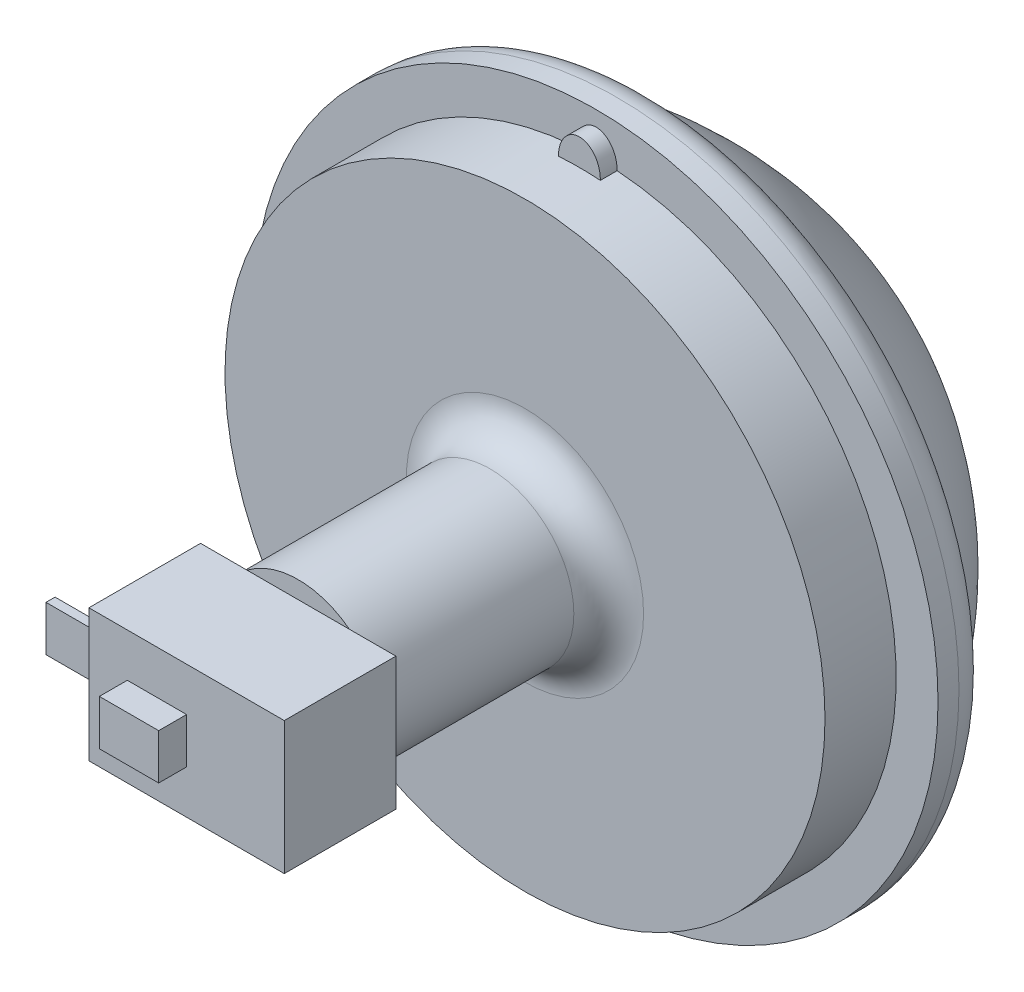
SolidWorks part; units mm, degrees
ref_plane "Front Plane" through (0, 0, 0) normal (0, 0, 1) x (1, 0, 0)
ref_plane "Top Plane" through (0, 0, 0) normal (0, 1, 0) x (1, 0, 0)
ref_plane "Right Plane" through (0, 0, 0) normal (1, 0, 0) x (0, 0, -1)
sketch "Sketch1" plane through (0, 0, 0) normal (0, 0, 1) x (1, 0, 0)
  circle A0 centre (0, 0) radius 49
  dimension "D1" = 98
extrude "Boss-Extrude1" add sketch "Sketch1" against normal blind 8
fillet "Fillet1" radius 5 1 edges at (49, 0, -8)
sketch "Sketch2" plane through (0, 0, 0) normal (0, 0, 1) x (1, 0, 0)
  circle A0 centre (0, 0) radius 43
  dimension "D1" = 86
extrude "Boss-Extrude2" add sketch "Sketch2" along normal blind 10.2
sketch "Sketch3" plane through (0, 0, 10.2) normal (0, 0, 1) x (1, 0, 0)
  circle A0 centre (0, 0) radius 12
  dimension "D1" = 24
extrude "Boss-Extrude3" add sketch "Sketch3" along normal blind 32.5
fillet "Fillet2" radius 5 1 edges at (12, 0, 10.2)
sketch "Sketch4" plane through (0, 0, 42.7) normal (0, 0, 1) x (1, 0, 0)
  line L1 (-14, 9.5) -> (14, 9.5)
  line L2 (-14, 9.5) -> (-14, -9.5)
  line L3 (-14, -9.5) -> (14, -9.5)
  line L4 (14, 9.5) -> (14, -9.5)
  line L5 (-14, 9.5) -> (14, -9.5) construction
  line L6 (-14, -9.5) -> (14, 9.5) construction
  point P0 (0, 0)
  dimension "D1" = 19
  dimension "D2" = 28
extrude "Boss-Extrude4" add sketch "Sketch4" along normal blind 16
sketch "Sketch5" plane through (0, 0, 58.7) normal (0, 0, 1) x (1, 0, 0)
  line L0 (0, 9.5) -> (0, -9.5) construction
  line L1 (14, 9.5) -> (-14, 9.5) construction
  line L2 (-7.3314, -9.5) -> (7.3314, -9.5) construction
  line L3 (-14, -3.25) -> (14, -3.25) construction
  line L4 (-14, 9.5) -> (-14, -9.5) construction
  line L5 (14, -9.5) -> (14, 9.5) construction
  line L6 (-14, 0) -> (14, 0) construction
  line L7 (-14, 3.25) -> (14, 3.25) construction
  line L9 (0, 3.25) -> (-8.5, 3.25)
  line L10 (0, 3.25) -> (0, -3.25)
  line L11 (0, -3.25) -> (-8.5, -3.25)
  line L12 (-8.5, 3.25) -> (-8.5, -3.25)
  point P12 (0, 0)
  dimension "D1" = 3.25
  dimension "D2" = 8.5
extrude "Boss-Extrude5" add sketch "Sketch5" along normal blind 4
sketch "Sketch6" plane through (-14, 0, 0) normal (-1, 0, 0) x (0, 0, 1)
  line L0 (54.2, 9.5) -> (54.2, -9.5) construction
  line L1 (58.7, 9.5) -> (42.7, 9.5) construction
  line L2 (58.7, -9.5) -> (42.7, -9.5) construction
  line L4 (53.55, 3.25) -> (54.85, 3.25)
  line L5 (53.55, 3.25) -> (53.55, -3.25)
  line L6 (53.55, -3.25) -> (54.85, -3.25)
  line L7 (54.85, 3.25) -> (54.85, -3.25)
  line L8 (53.55, 3.25) -> (54.85, -3.25) construction
  line L9 (53.55, -3.25) -> (54.85, 3.25) construction
  point P6 (54.2, 0)
  dimension "D1" = 4.5
  dimension "D2" = 1.3
  dimension "D3" = 6.5
extrude "Boss-Extrude6" add sketch "Sketch6" along normal blind 10
sketch "Sketch7" plane through (0, 0, 0) normal (0, 0, 1) x (1, 0, 0)
  line L0 (0, 49) -> (0, -49) construction
  line L1 (-49, 0) -> (49, 0) construction
  circle A0 centre (0, 0) radius 43 construction
  circle A1 centre (0, 0) radius 43
  circle A2 centre (0, 0) radius 49 construction
  circle A3 centre (0, 0) radius 49
  ellipse E0 centre (0, 43) end of major axis (0, 39.2) minor radius 3
  ellipse E1 centre (0, -43) end of major axis (0, -39.2) minor radius 3
extrude "Boss-Extrude7" add sketch "Sketch7" along normal blind 2.4 contours E1 | E0
sketch "Sketch9" plane through (0, 0, 0) normal (1, 0, 0) x (0, 0, -1)
  line L0 (8, 0) -> (63.5849, 0) construction
  line L1 (8, -44) -> (8, 44) construction
  line L3 (8, -44) -> (8, 44)
  line L5 (8, 0) -> (35, 0)
  arc A3 (8, -44) -> (35, 0) centre (-18.3435, 2.4494) ccw
  dimension "D1" = 27
revolve "Revolve4" add sketch "Sketch9" angle 360 about L0
